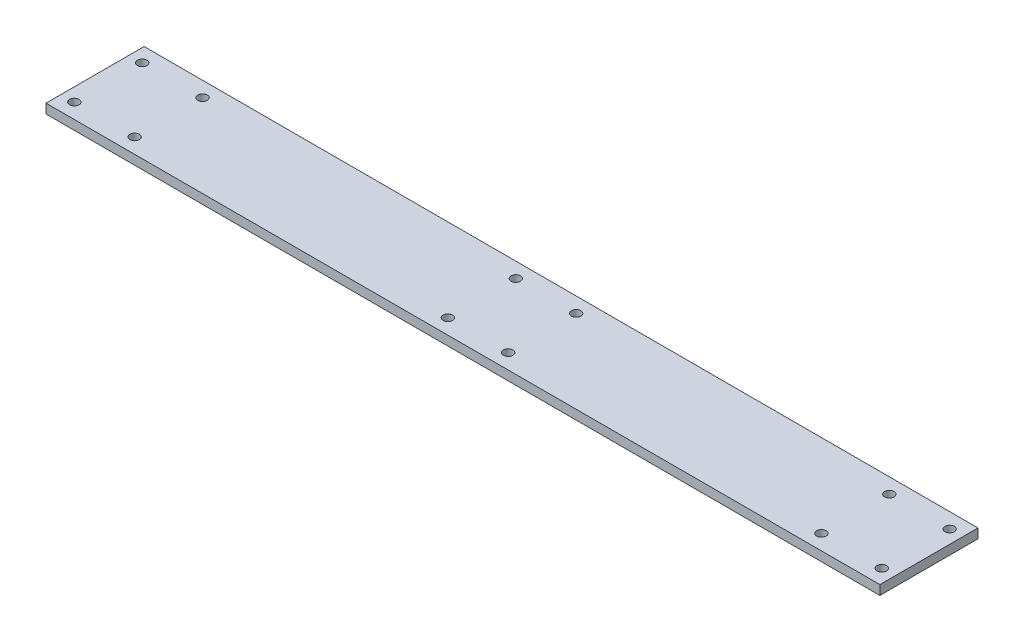
SolidWorks part; units mm, degrees
ref_plane "前视基准面" through (0, 0, 0) normal (0, 0, 1) x (1, 0, 0)
ref_plane "上视基准面" through (0, 0, 0) normal (0, 1, 0) x (1, 0, 0)
ref_plane "右视基准面" through (0, 0, 0) normal (1, 0, 0) x (0, 0, -1)
sketch "草图1" plane through (0, 0, 0) normal (0, 1, 0) x (1, 0, 0)
  line L1 (0, 0) -> (442, 0)
  line L2 (0, 0) -> (0, 52)
  line L3 (0, 52) -> (442, 52)
  line L4 (442, 0) -> (442, 52)
  dimension "D1" = 442
  dimension "D2" = 52
extrude "凸台-拉伸1" add sketch "草图1" along normal blind 5
sketch "草图2" plane through (0, 5, 0) normal (0, 1, 0) x (1, 0, 0)
  line L0 (221, 0) -> (221, 52) construction
  line L1 (0, 0) -> (442, 0) construction
  line L2 (442, 52) -> (0, 52) construction
  line L3 (0, 26) -> (442, 26) construction
  line L4 (0, 52) -> (0, 0) construction
  line L5 (442, 0) -> (442, 52) construction
  line L6 (419, 0) -> (419, 52) construction
  line L7 (23, 0) -> (23, 52) construction
  circle A0 centre (205, 8) radius 2.5
  circle A1 centre (237, 8) radius 2.5
  circle A2 centre (205, 44) radius 2.5
  circle A3 centre (237, 44) radius 2.5
  circle A4 centre (435, 44) radius 2.5
  circle A5 centre (403, 44) radius 2.5
  circle A6 centre (403, 8) radius 2.5
  circle A7 centre (435, 8) radius 2.5
  circle A8 centre (7, 44) radius 2.5
  circle A9 centre (39, 44) radius 2.5
  circle A10 centre (39, 8) radius 2.5
  circle A11 centre (7, 8) radius 2.5
  dimension "D2" = 36
  dimension "D3" = 32
  dimension "D4" = 5
  dimension "D1" = 23
extrude "切除-拉伸1" cut sketch "草图2" against normal through all
